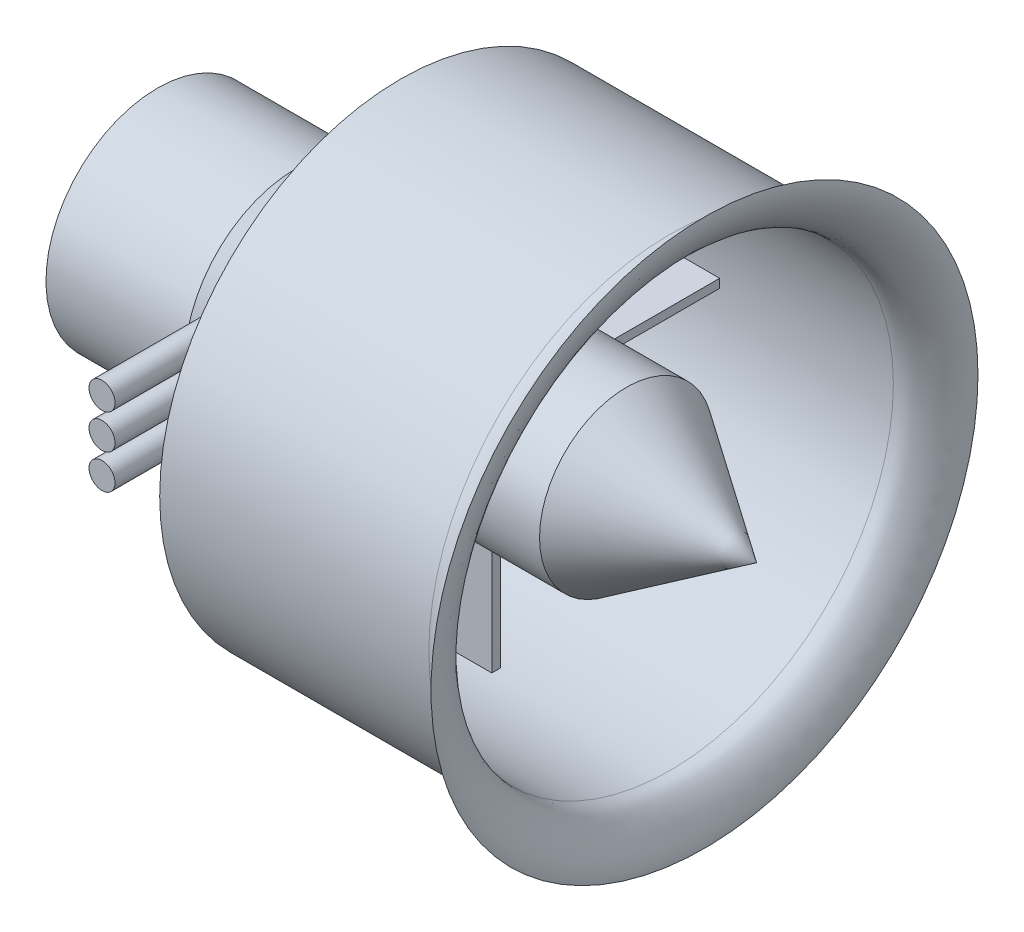
SolidWorks part; units mm, degrees
ref_plane "Plan de face" through (0, 0, 0) normal (0, 0, 1) x (1, 0, 0)
ref_plane "Plan de dessus" through (0, 0, 0) normal (0, 1, 0) x (1, 0, 0)
ref_plane "Plan de droite" through (0, 0, 0) normal (1, 0, 0) x (0, 0, -1)
sketch "Esquisse1" plane through (0, 0, 0) normal (0, 0, 1) x (1, 0, 0)
  line L0 (0, 0) -> (-11.5963, 0) construction
  line L1 (-18.797, 27.75) -> (12.203, 27.75)
  line L2 (-18.797, 27.75) -> (-18.797, 25.75)
  line L3 (-18.797, 25.75) -> (12.203, 25.75)
  line L4 (12.203, 27.75) -> (12.203, 25.75) construction
  arc A0 (12.203, 27.75) -> (16.203, 31.5) centre (12.203, 31.7583) ccw
  spline S0 degree 3 poles (12.203, 25.75) (13.3109, 25.75) (14.9417, 27.132) (16.4652, 29.7494) (16.203, 31.5) knots 0 0 0 0 0.303787 1 1 1 1
  dimension "D1" = 2
  dimension "D2" = 31
  dimension "D3" = 35
  dimension "D4" = 31.5
  dimension "D5" = 27.75
revolve "Révolution1" add sketch "Esquisse1" angle 360 about L0
sketch "Esquisse2" plane through (0, 0, 0) normal (0, 0, 1) x (1, 0, 0)
  line L0 (22.203, 0) -> (7.203, 10)
  line L1 (7.203, 10) -> (7.203, 0) construction
  line L2 (7.203, 0) -> (22.203, 0)
  line L3 (16.203, 31.5) -> (16.203, -31.5) construction
  line L4 (7.203, 10) -> (-25.797, 10)
  line L5 (7.203, 0) -> (-25.797, 0)
  line L6 (-25.797, 0) -> (-25.797, 10)
  line L7 (-18.797, 27.75) -> (-18.797, -27.75) construction
  dimension "D1" = 10
  dimension "D2" = 6
  dimension "D3" = 9
  dimension "D4" = 7
revolve "Révolution2" add sketch "Esquisse2" angle 360 about L2
sketch "Esquisse3" plane through (0, 0, 0) normal (0, 0, 1) x (1, 0, 0)
  line L0 (-25.797, 10) -> (-18.797, 25.75)
  line L1 (-18.797, 25.75) -> (-7.797, 25.75)
  line L2 (-7.797, 25.75) -> (-7.797, 10)
  line L3 (-7.797, 10) -> (-25.797, 10)
  dimension "D1" = 11
extrude "Boss.-Extru.1" add sketch "Esquisse3" along normal mid plane 1
pattern_circular "Répétition circulaire1" count 8 over 360 about axis through (0, 0, 0) along (1, 0, 0) of "Boss.-Extru.1"
sketch "Esquisse4" plane through (0, 0, 0) normal (0, 0, 1) x (1, 0, 0)
  line L0 (0, 0) -> (-54.297, 0) construction
  line L1 (-54.297, 0) -> (-54.297, 1.5)
  line L2 (-52.097, 1.5) -> (-52.097, 4.5)
  line L3 (-52.097, 4.5) -> (-50.097, 4.5)
  line L4 (-50.097, 4.5) -> (-50.097, 6.3623)
  line L5 (-50.097, 6.3623) -> (-46.797, 11.0588)
  line L6 (-46.797, 11.0588) -> (-46.797, 12.85)
  line L7 (-46.797, 12.85) -> (-30.797, 12.85)
  line L8 (-30.797, 12.85) -> (-25.797, 10)
  line L9 (-25.797, 10) -> (-25.797, -10) construction
  line L10 (-25.797, 10) -> (-25.797, 0)
  line L11 (-25.797, 0) -> (-54.297, 0)
  line L12 (-54.297, 1.5) -> (-52.097, 1.5)
  dimension "D1" = 28.5
  dimension "D2" = 1.5
  dimension "D3" = 2.2
  dimension "D4" = 4.5
  dimension "D5" = 2
  dimension "D6" = 12.85
  dimension "D7" = 16
  dimension "D8" = 5
  dimension "D9" = 10
revolve "Révolution3" add sketch "Esquisse4" angle 360 about L0
sketch "Esquisse5" plane through (0, 0, 0) normal (0, 0, 1) x (1, 0, 0)
  line L0 (0, 0) -> (-28.1891, 0) construction
  circle A0 centre (-28.1891, 0) radius 1.5
  circle A1 centre (-28.1891, -4) radius 1.5
  circle A2 centre (-28.1891, 4) radius 1.5
  dimension "D1" = 3
  dimension "D2" = 4
extrude "Boss.-Extru.2" add sketch "Esquisse5" along normal blind 25
